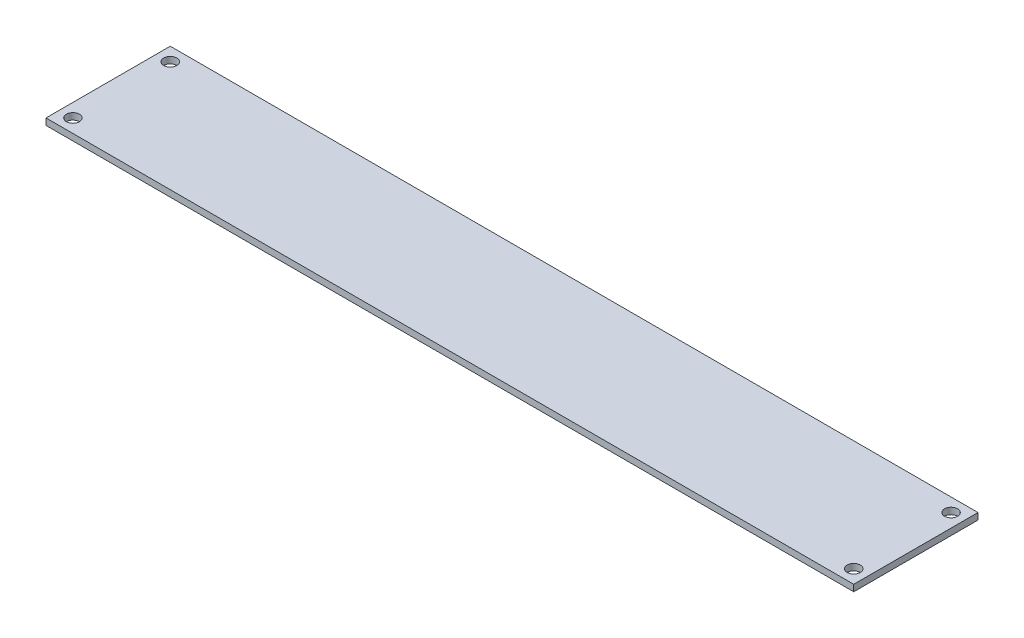
SolidWorks part; units mm, degrees
ref_plane "Front Plane" through (0, 0, 0) normal (0, 0, 1) x (1, 0, 0)
ref_plane "Top Plane" through (0, 0, 0) normal (0, 1, 0) x (1, 0, 0)
ref_plane "Right Plane" through (0, 0, 0) normal (1, 0, 0) x (0, 0, -1)
sketch "Sketch1" plane through (0, 0, 0) normal (0, 1, 0) x (1, 0, 0)
  line L0 (-99.06, 15.24) -> (-95.7585, 11.9385) construction
  line L1 (-99.06, 15.24) -> (99.06, 15.24)
  line L2 (-99.06, 15.24) -> (-99.06, -15.24)
  line L3 (-99.06, -15.24) -> (99.06, -15.24)
  line L4 (99.06, 15.24) -> (99.06, -15.24)
  line L5 (-99.06, 15.24) -> (99.06, -15.24) construction
  line L6 (-99.06, -15.24) -> (99.06, 15.24) construction
  line L7 (0, 15.24) -> (0, -15.24) construction
  line L8 (-99.06, 0) -> (99.06, 0) construction
  line L9 (-99.06, -15.24) -> (-95.7585, -11.9385) construction
  line L10 (99.06, -15.24) -> (95.7585, -11.9385) construction
  line L11 (99.06, 15.24) -> (95.7585, 11.9385) construction
  circle A0 centre (-95.7585, 11.9385) radius 1.6
  circle A1 centre (-95.7585, -11.9385) radius 1.6
  circle A2 centre (95.7585, -11.9385) radius 1.6
  circle A3 centre (95.7585, 11.9385) radius 1.6
  point P0 (0, 0)
  dimension "D4" = 3.2
  dimension "D1" = 30.48
  dimension "D2" = 198.12
  dimension "D3" = 4.669
extrude "Boss-Extrude1" add sketch "Sketch1" along normal blind 1.6
